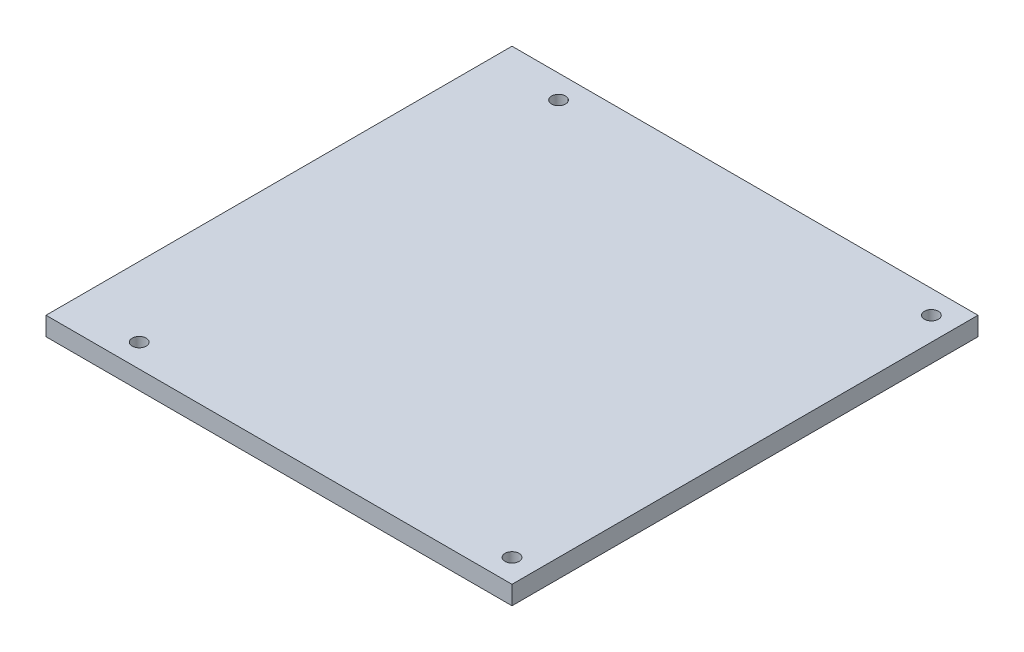
SolidWorks part; units mm, degrees
ref_plane "Alzado" through (0, 0, 0) normal (0, 0, 1) x (1, 0, 0)
ref_plane "Planta" through (0, 0, 0) normal (0, 1, 0) x (1, 0, 0)
ref_plane "Vista lateral" through (0, 0, 0) normal (1, 0, 0) x (0, 0, -1)
sketch "Croquis1" plane through (0, 0, 0) normal (0, 1, 0) x (1, 0, 0)
  line L1 (0, 0) -> (100, 0)
  line L2 (0, 0) -> (0, -100)
  line L3 (0, -100) -> (100, -100)
  line L4 (100, 0) -> (100, -100)
  dimension "D1" = 100
  dimension "D2" = 100
extrude "Saliente-Extruir1" add sketch "Croquis1" along normal blind 4
sketch "Croquis2" plane through (0, 4, 0) normal (0, 1, 0) x (1, 0, 0)
  line L0 (0, 0) -> (0, -100) construction
  line L1 (100, 0) -> (0, 0) construction
  line L2 (100, -100) -> (100, 0) construction
  line L3 (0, -100) -> (100, -100) construction
  circle A0 centre (15, -5) radius 1.5
  circle A1 centre (95, -5) radius 1.5
  circle A2 centre (15, -95) radius 1.5
  circle A3 centre (95, -95) radius 1.5
  dimension "D1" = 3
  dimension "D2" = 3
  dimension "D3" = 3
  dimension "D4" = 3
  dimension "D5" = 15
  dimension "D6" = 5
  dimension "D7" = 5
  dimension "D8" = 5
  dimension "D9" = 5
  dimension "D10" = 15
  dimension "D11" = 5
  dimension "D12" = 5
extrude "Cortar-Extruir1" cut sketch "Croquis2" against normal through all
